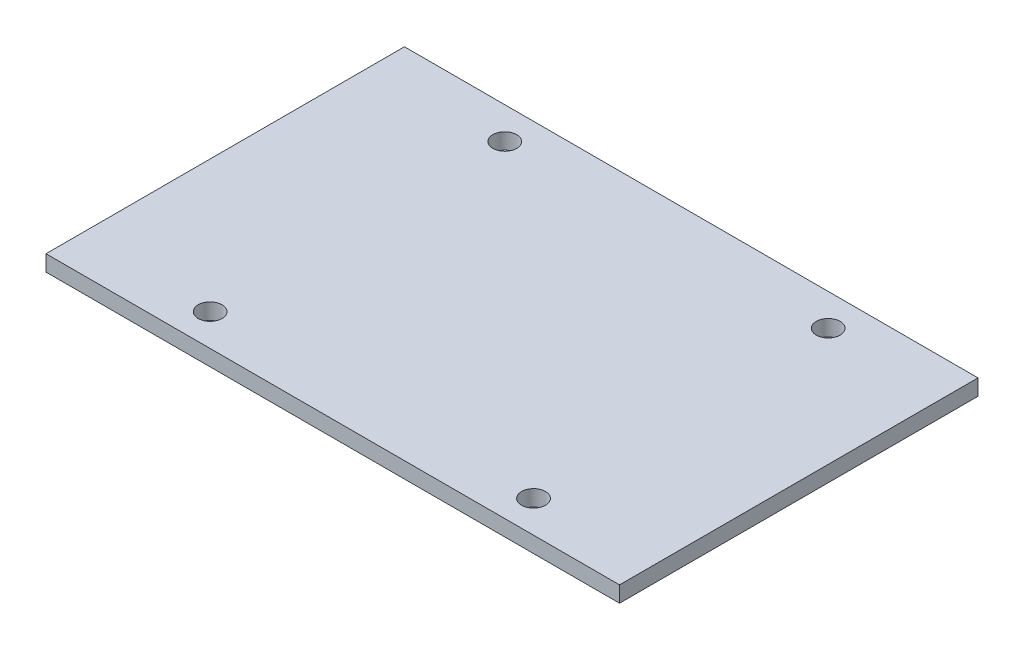
SolidWorks part; units mm, degrees
ref_plane "Front Plane" through (0, 0, 0) normal (0, 0, 1) x (1, 0, 0)
ref_plane "Top Plane" through (0, 0, 0) normal (0, 1, 0) x (1, 0, 0)
ref_plane "Right Plane" through (0, 0, 0) normal (1, 0, 0) x (0, 0, -1)
sketch "Sketch1" plane through (0, 0, 0) normal (0, 1, 0) x (1, 0, 0)
  line L1 (-36, -22.5) -> (36, -22.5)
  line L2 (-36, -22.5) -> (-36, 22.5)
  line L3 (-36, 22.5) -> (36, 22.5)
  line L4 (36, -22.5) -> (36, 22.5)
  line L5 (-36, -22.5) -> (36, 22.5) construction
  line L6 (-36, 22.5) -> (36, -22.5) construction
  point P0 (0, 0)
  dimension "D1" = 45
  dimension "D2" = 72
extrude "Boss-Extrude1" add sketch "Sketch1" along normal blind 2
sketch "Sketch2" plane through (0, 2, 0) normal (0, 1, 0) x (1, 0, 0)
  line L0 (-36, 0) -> (36, 0) construction
  line L1 (-19.4, -18.495) -> (21.2, -18.495) construction
  line L2 (-19.4, -18.495) -> (-19.4, 18.495) construction
  line L3 (-19.4, 18.495) -> (21.2, 18.495) construction
  line L4 (21.2, -18.495) -> (21.2, 18.495) construction
  line L5 (-19.4, -18.495) -> (21.2, 18.495) construction
  line L6 (-19.4, 18.495) -> (21.2, -18.495) construction
  line L7 (-36, 22.5) -> (-36, -22.5) construction
  line L8 (36, -22.5) -> (36, 22.5) construction
  circle A0 centre (21.2, 18.495) radius 1.5
  circle A1 centre (21.2, -18.495) radius 1.5
  circle A2 centre (-19.4, -18.495) radius 1.5
  circle A3 centre (-19.4, 18.495) radius 1.5
  point P0 (0, 0)
  point P10 (-20.9, 18.495)
  point P11 (-19.4, 19.995)
  point P12 (21.2, 19.995)
  point P13 (-19.4, -19.995)
  point P14 (22.7, 18.495)
  point P20 (-19.4, 0)
  dimension "D1" = 3
  dimension "D2" = 43.6
  dimension "D3" = 39.99
  dimension "D4" = 16.6
extrude "Cut-Extrude1" cut sketch "Sketch2" against normal blind 2 contours A3
